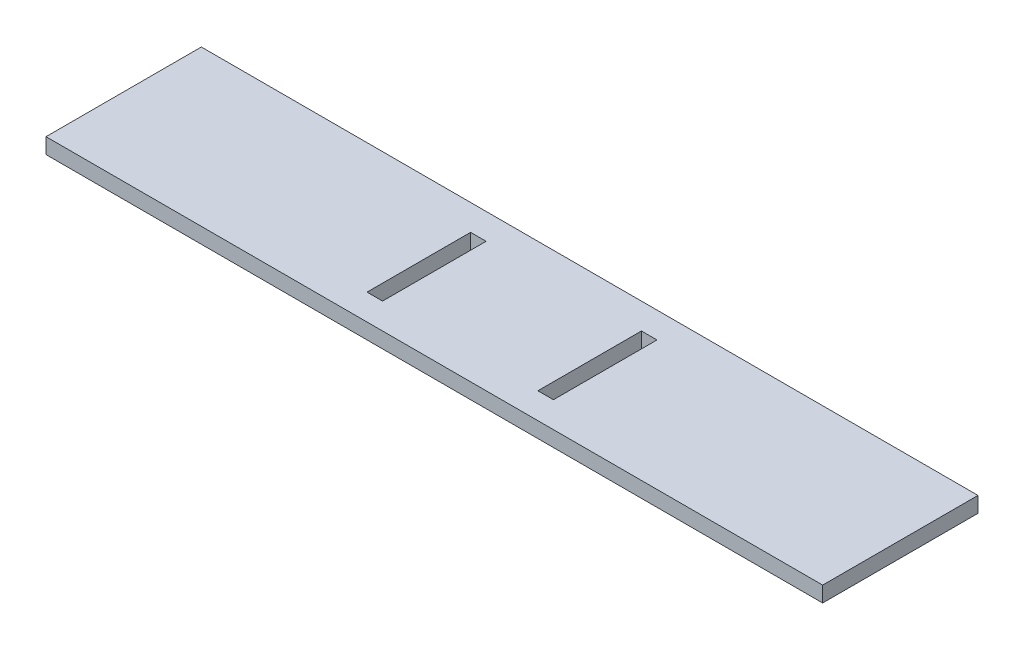
SolidWorks part; units mm, degrees
ref_plane "Plano frontal" through (0, 0, 0) normal (0, 0, 1) x (1, 0, 0)
ref_plane "Plano superior" through (0, 0, 0) normal (0, 1, 0) x (1, 0, 0)
ref_plane "Plano direito" through (0, 0, 0) normal (1, 0, 0) x (0, 0, -1)
sketch "Esboço1" plane through (0, 0, 0) normal (0, 1, 0) x (1, 0, 0)
  line L1 (0, 0) -> (150, 0)
  line L2 (0, 0) -> (0, 30)
  line L3 (0, 30) -> (150, 30)
  line L4 (150, 0) -> (150, 30)
  line L6 (90, 25) -> (93, 25)
  line L7 (60, 5) -> (57, 5)
  line L8 (60, 5) -> (60, 25)
  line L9 (60, 25) -> (57, 25)
  line L10 (57, 5) -> (57, 25)
  line L11 (90, 5) -> (90, 25)
  line L12 (90, 5) -> (93, 5)
  line L13 (93, 5) -> (93, 25)
  point P5 (57, 15)
  dimension "D1" = 150
  dimension "D2" = 30
  dimension "D3" = 36
  dimension "D4" = 57
  dimension "D5" = 20
  dimension "D6" = 5
  dimension "D7" = 3
extrude "Ressalto-extrusão1" add sketch "Esboço1" along normal blind 3
